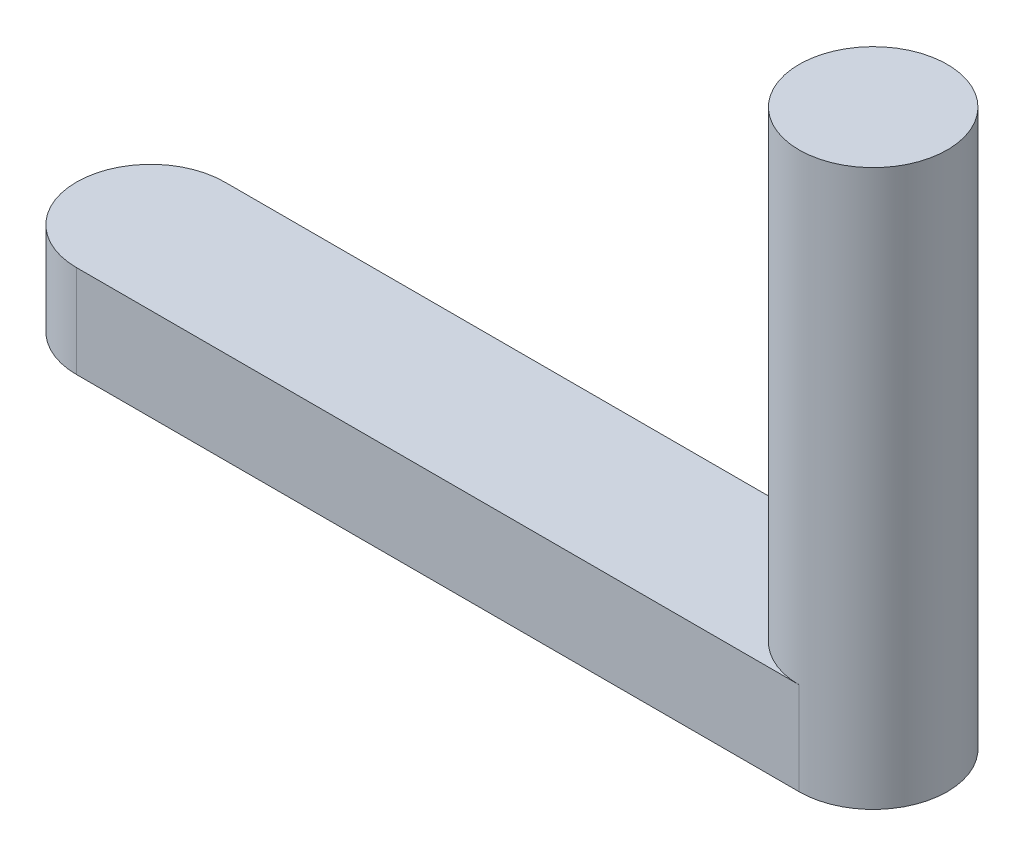
SolidWorks part; units mm, degrees
ref_plane "Front Plane" through (0, 0, 0) normal (0, 0, 1) x (1, 0, 0)
ref_plane "Top Plane" through (0, 0, 0) normal (0, 1, 0) x (1, 0, 0)
ref_plane "Right Plane" through (0, 0, 0) normal (1, 0, 0) x (0, 0, -1)
sketch "Sketch1" plane through (0, 0, 0) normal (0, 1, 0) x (1, 0, 0)
  line L1 (0, 0) -> (39, 0)
  line L3 (0, -8) -> (39, -8)
  arc A0 (0, 0) -> (0, -8) centre (0, -4) ccw
  arc A1 (39, -8) -> (39, 0) centre (39, -4) ccw
  point P7 (46.3333, -7.727)
  point P9 (34.2222, -8)
  point P10 (0, 0)
  point P11 (38.3333, -8)
  point P12 (0, 0)
  point P13 (0, 0)
  point P14 (0, 0)
  point P15 (0, 0)
  point P16 (-8.2222, -20.5556)
  dimension "D2" = 4
  dimension "D1" = 8
  dimension "D3" = 39
extrude "Boss-Extrude1" add sketch "Sketch1" along normal blind 5
sketch "Sketch2" plane through (0, 0, 0) normal (0, 1, 0) x (1, 0, 0)
  circle A0 centre (0, -4) radius 2.525
  dimension "D1" = 5.05
extrude "Cut-Extrude1" cut sketch "Sketch2" along normal blind 2
sketch "Sketch3" plane through (0, 0, 0) normal (0, 1, 0) x (1, 0, 0)
  circle A0 centre (39, -4) radius 4
extrude "Boss-Extrude2" add sketch "Sketch3" along normal blind 30
